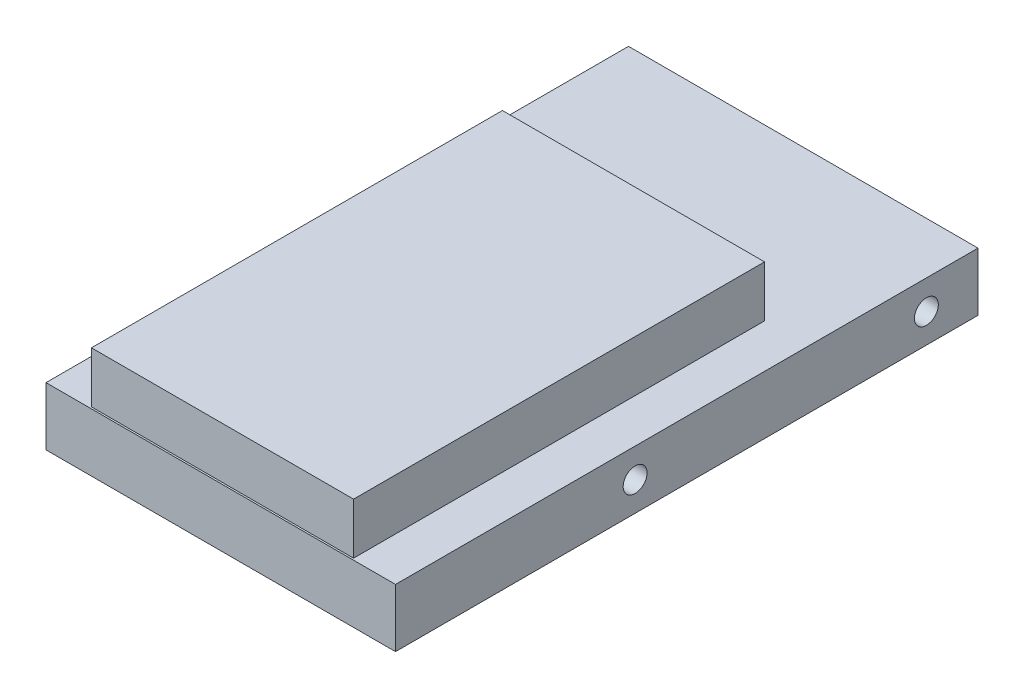
SolidWorks part; units mm, degrees
ref_plane "정면" through (0, 0, 0) normal (0, 0, 1) x (1, 0, 0)
ref_plane "윗면" through (0, 0, 0) normal (0, 1, 0) x (1, 0, 0)
ref_plane "우측면" through (0, 0, 0) normal (1, 0, 0) x (0, 0, -1)
sketch "스케치1" plane through (0, 0, 0) normal (1, 0, 0) x (0, 0, -1)
  line L1 (0, 0) -> (100, 0)
  line L2 (0, 0) -> (0, 10)
  line L3 (0, 10) -> (100, 10)
  line L4 (100, 0) -> (100, 10)
  dimension "D1" = 10
  dimension "D2" = 100
extrude "보스-돌출1" add sketch "스케치1" along normal mid plane 60
sketch "스케치2" plane through (0, 0, 0) normal (1, 0, 0) x (0, 0, -1)
  line L0 (41.138, 5) -> (91.138, 5) construction
  circle A0 centre (41.138, 5) radius 2.05
  circle A1 centre (91.138, 5) radius 2.05
  dimension "D1" = 4.1
  dimension "D2" = 4.1
  dimension "D3" = 50
  dimension "D4" = 5
extrude "컷-돌출1" cut sketch "스케치2" against normal through all both and the other way through all
sketch "스케치4" plane through (0, 0, 0) normal (1, 0, 0) x (0, 0, -1)
  line L0 (100, 10) -> (0, 10) construction
  line L1 (0.3004, 10) -> (70.8527, 10)
  line L2 (0.3004, 10) -> (0.3004, 18.7794)
  line L3 (0.3004, 18.7794) -> (70.8527, 18.7794)
  line L4 (70.8527, 10) -> (70.8527, 18.7794)
extrude "보스-돌출2" add sketch "스케치4" along normal mid plane 45
